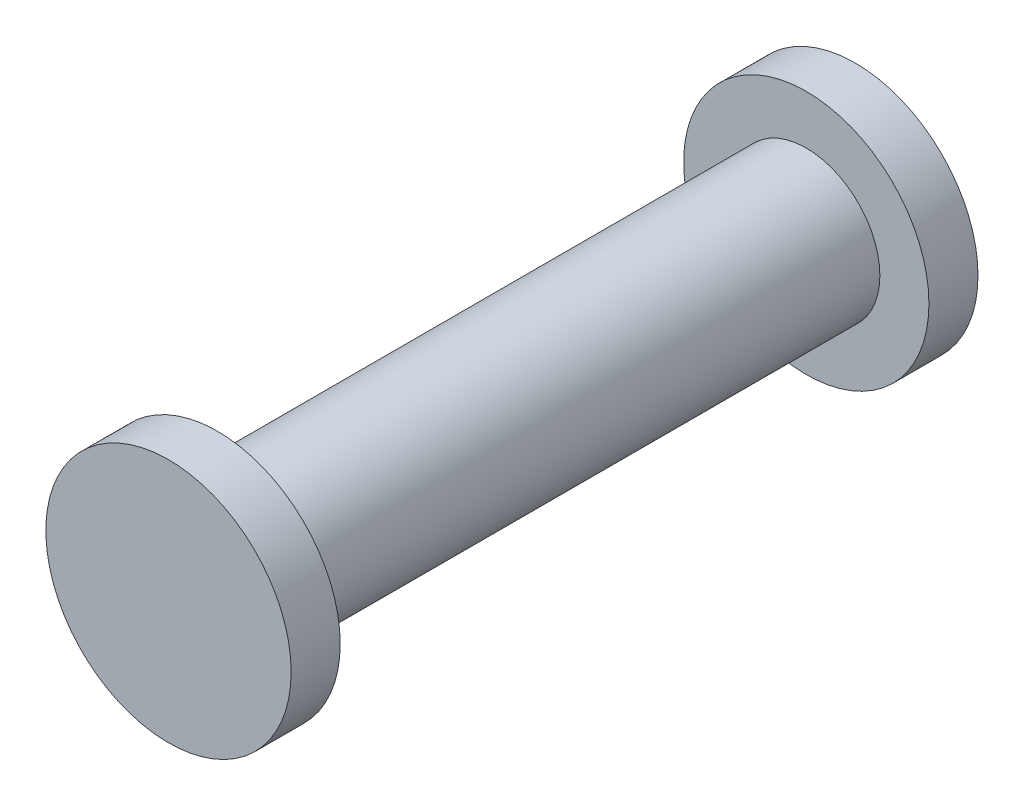
SolidWorks part; units mm, degrees
ref_plane "Front Plane" through (0, 0, 0) normal (0, 0, 1) x (1, 0, 0)
ref_plane "Top Plane" through (0, 0, 0) normal (0, 1, 0) x (1, 0, 0)
ref_plane "Right Plane" through (0, 0, 0) normal (1, 0, 0) x (0, 0, -1)
sketch "Sketch1" plane through (0, 0, 0) normal (0, 0, 1) x (1, 0, 0)
  circle A0 centre (0, 0) radius 2.5
  dimension "D1" = 5
extrude "Boss-Extrude1" add sketch "Sketch1" along normal blind 1
sketch "Sketch2" plane through (0, 0, 1) normal (0, 0, 1) x (1, 0, 0)
  circle A0 centre (0, 0) radius 1.5
  dimension "D1" = 3
extrude "Boss-Extrude2" add sketch "Sketch2" along normal blind 12
sketch "Sketch3" plane through (0, 0, 13) normal (0, 0, 1) x (1, 0, 0)
  circle A0 centre (0, 0) radius 2.5
  dimension "D1" = 5
extrude "Boss-Extrude3" add sketch "Sketch3" along normal blind 1
